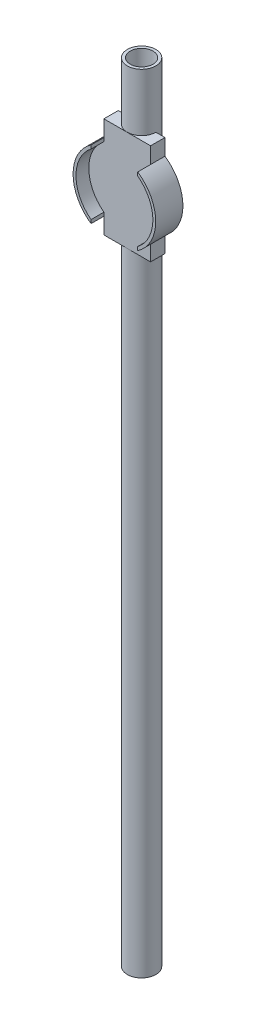
SolidWorks part; units mm, degrees
ref_plane "Front Plane" through (0, 0, 0) normal (0, 0, 1) x (1, 0, 0)
ref_plane "Top Plane" through (0, 0, 0) normal (0, 1, 0) x (1, 0, 0)
ref_plane "Right Plane" through (0, 0, 0) normal (1, 0, 0) x (0, 0, -1)
sketch "Sketch1" plane through (0, 0, 0) normal (0, 0, 1) x (1, 0, 0)
  line L14 (0, 0) -> (0, -224.1684) construction
  line L16 (-26.9875, -300.3684) -> (26.9875, -300.3684) construction
  line L17 (3.175, -300.3684) -> (3.975, -300.3684)
  line L18 (3.175, -300.3684) -> (3.175, -81.28)
  line L19 (3.175, -81.28) -> (3.975, -81.28)
  line L20 (3.975, -300.3684) -> (3.975, -81.28)
  line L21 (3.175, -304.8853) -> (3.175, -76.2853) construction
  line L22 (-9.525, -81.28) -> (9.525, -81.28) construction
  dimension "D1" = 0.8
revolve "Revolve1" add sketch "Sketch1" angle 360 about L14
sketch "Sketch17" plane through (0, 58.9002, 0) normal (0, 0, 1) x (1, 0, 0)
  line L0 (-9.525, -140.1802) -> (9.525, -140.1802) construction
  line L1 (-6.5, -156.1802) -> (6.5, -156.1802)
  line L2 (-6.5, -156.1802) -> (-6.5, -184.1802)
  line L3 (-6.5, -184.1802) -> (6.5, -184.1802)
  line L4 (6.5, -156.1802) -> (6.5, -184.1802)
  line L5 (-6.5, -156.1802) -> (6.5, -184.1802) construction
  line L6 (-6.5, -184.1802) -> (6.5, -156.1802) construction
  circle A0 centre (0, -170.1802) radius 11.5
  point P0 (0, -170.1802)
  dimension "D4" = 23
  dimension "D1" = 13
  dimension "D2" = 16
  dimension "D3" = 28
extrude "Boss-Extrude2" add sketch "Sketch17" along normal blind 4 contours L4 A0 L2 | L2 A0 | A0 L4 L1 L2 | L4 A0 | A0 L2 L3 L4
sketch "Sketch18" plane through (0, 0, 4) normal (0, 0, 1) x (1, 0, 0)
  line L1 (-6.5, -125.28) -> (6.5, -125.28)
  line L2 (-6.5, -125.28) -> (-6.5, -97.28)
  line L3 (-6.5, -97.28) -> (6.5, -97.28)
  line L4 (6.5, -125.28) -> (6.5, -97.28)
  circle A0 centre (0, -111.28) radius 11.5
  arc A1 (-6.5, -101.7932) -> (-6.5, -120.7668) centre (0, -111.28) ccw construction
  circle A2 centre (0, -111.28) radius 10.7
  arc M4 (-6.5, -101.7932) -> (-6.5, -120.7668) centre (0, -111.28) ccw
  dimension "D1" = 0.8
extrude "Boss-Extrude3" add sketch "Sketch18" along normal blind 3.575 contours A2 L2 M4 | A2 L4 A0
